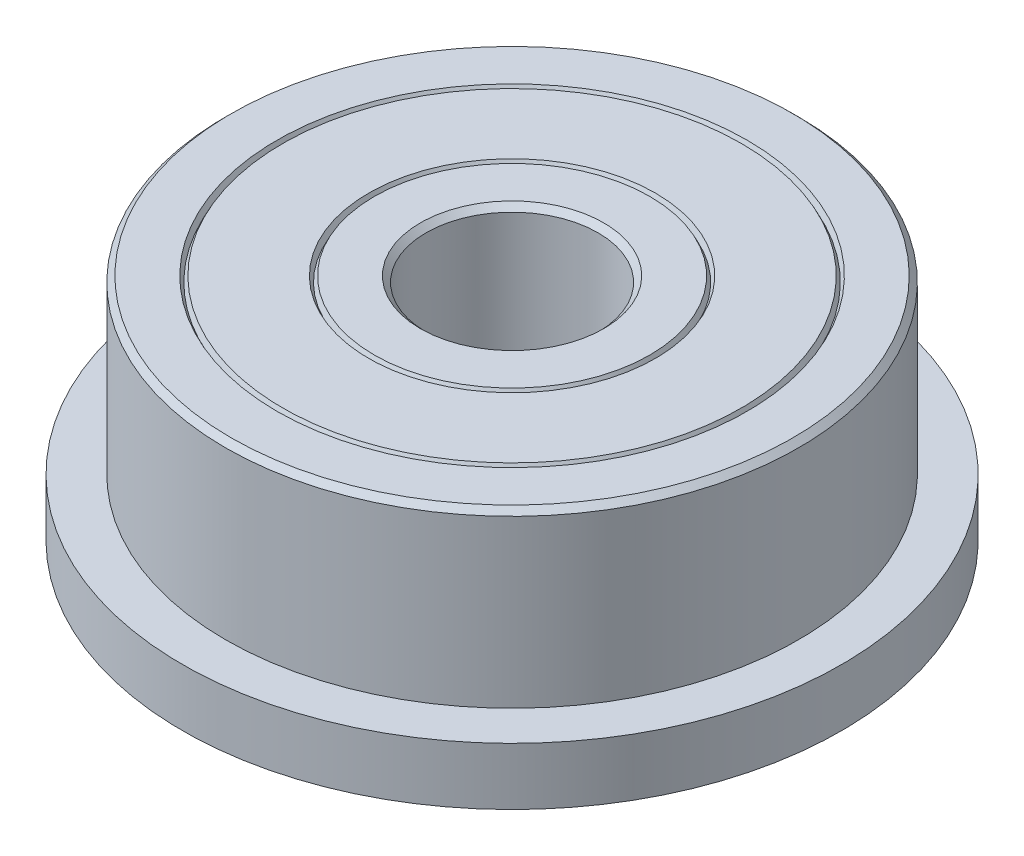
SolidWorks part; units mm, degrees
material "Chrome Stainless Steel"
ref_plane "Front" through (0, 0, 0) normal (0, 0, 1) x (1, 0, 0)
ref_plane "Top" through (0, 0, 0) normal (0, 1, 0) x (1, 0, 0)
ref_plane "Right" through (0, 0, 0) normal (1, 0, 0) x (0, 0, -1)
sketch "Sketch1" plane through (0, 0, 0) normal (1, 0, 0) x (0, 0, -1)
  line L2 (5, -1) -> (5, 2)
  line L5 (0, -2) -> (0, 2) construction
  line L6 (0, 2) -> (1.5, 2) construction
  line L9 (5, -1) -> (5.75, -1)
  line L10 (5.75, -2) -> (5.75, -1)
  line L11 (0, -2) -> (1.5, -2) construction
  line L12 (5, 2) -> (4.0996, 2)
  line L13 (1.5, 2) -> (1.5, -2)
  line L14 (1.5, -2) -> (2.4004, -2)
  line L15 (3.25, 2) -> (3.25, 0) construction
  line L16 (4.0496, 1.9) -> (4.0996, 2)
  line L17 (2.5004, 2) -> (2.4504, 1.9)
  line L18 (2.4504, 1.9) -> (2.4004, 2)
  line L19 (3.9996, 2) -> (4.0496, 1.9)
  line L20 (2.4004, 2) -> (1.5, 2)
  line L21 (3.9996, 2) -> (2.5004, 2)
  line L22 (1.5, 0) -> (3.25, 0) construction
  line L23 (4.0496, -1.9) -> (4.0996, -2)
  line L24 (3.9996, -2) -> (4.0496, -1.9)
  line L25 (2.4504, -1.9) -> (2.4004, -2)
  line L26 (2.5004, -2) -> (2.4504, -1.9)
  line L27 (2.5004, -2) -> (3.9996, -2)
  line L28 (4.0996, -2) -> (5.75, -2)
  point P4 (0, 0)
  point P13 (1.5, 0)
  dimension "D1" = 3
  dimension "D2" = 5.75
  dimension "D3" = 1
  dimension "D4" = 5
  dimension "D5" = 1.5
  dimension "D6" = 0.7496
  dimension "D7" = 0.1
  dimension "D8" = 0.1
  dimension "D9" = 1.75
revolve "Revolve1" add sketch "Sketch1" angle 360 about L5
chamfer "Chamfer1" distance 0.1 angle 45 3 edges at (0, -2, -1.5) (0, 2, -5) (0, 2, -1.5)
